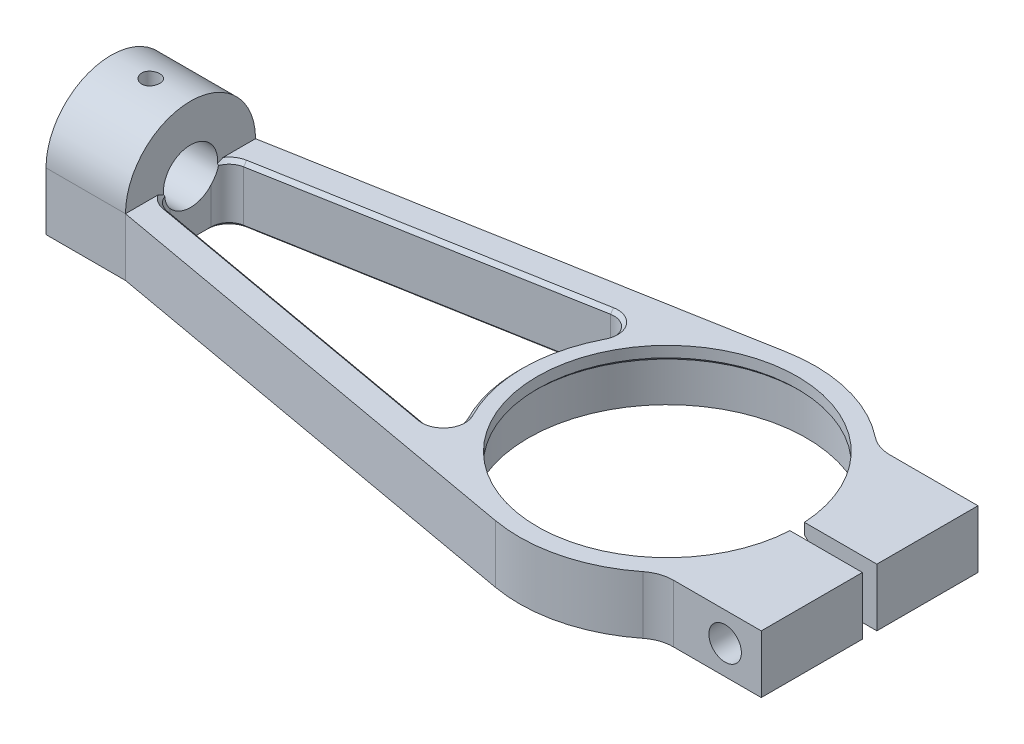
SolidWorks part; units mm, degrees
ref_plane "前视基准面" through (0, 0, 0) normal (0, 0, 1) x (1, 0, 0)
ref_plane "上视基准面" through (0, 0, 0) normal (0, 1, 0) x (1, 0, 0)
ref_plane "右视基准面" through (0, 0, 0) normal (1, 0, 0) x (0, 0, -1)
sketch "草图1" plane through (0, 0, 0) normal (0, 1, 0) x (1, 0, 0)
  line L0 (-55, 0) -> (55, 0) construction
  line L1 (56, -30) -> (27.9464, -30)
  line L2 (56, -30) -> (56, 30)
  line L3 (56, 30) -> (27.9464, 30)
  line L4 (27.9464, -30) -> (27.9464, 30) construction
  line L5 (56, -30) -> (40.9405, 2.2088) construction
  line L6 (56, 30) -> (40.9405, -2.2088) construction
  line L7 (-7.2316, 40.3572) -> (-132, 18)
  line L8 (-132, 18) -> (-132, -18)
  line L9 (-132, 0) -> (0, 0) construction
  line L10 (-7.2316, -40.3572) -> (-132, -18)
  line L11 (40.9405, 2.2088) -> (27.9464, 30) construction
  line L12 (40.9405, -2.2088) -> (27.9464, -30) construction
  line L13 (0, -55) -> (0, 55) construction
  line L14 (-132, -18) -> (-154, -18) construction
  line L15 (-132, -18) -> (-132, 18)
  line L16 (-132, 18) -> (-154, 18) construction
  line L17 (-154, -18) -> (-154, 18) construction
  arc A0 (-7.2316, -40.3572) -> (27.9464, -30) centre (0, 0) ccw
  arc A1 (-7.2316, 40.3572) -> (-41, 0) centre (0, 0) ccw construction
  arc A2 (-41, 0) -> (-7.2316, -40.3572) centre (0, 0) ccw construction
  arc A3 (40.9405, -2.2088) -> (40.9405, 2.2088) centre (0, 0) ccw construction
  arc A4 (27.9464, 30) -> (-7.2316, 40.3572) centre (0, 0) ccw
  arc A5 (40.9405, 2.2088) -> (27.9464, 30) centre (0, 0) ccw construction
  arc A6 (27.9464, -30) -> (40.9405, -2.2088) centre (0, 0) ccw construction
  point P3 (41.9732, 0)
  point P20 (-138.0209, 17.4084)
  point P22 (0, 0)
  dimension "D1" = 82
  dimension "D2" = 60
  dimension "D3" = 22
  dimension "D4" = 154
  dimension "D5" = 210
  dimension "D6" = 36
extrude "凸台-拉伸1" add sketch "草图1" along normal blind 16 contours L3 A4 L7 L8 L10 A0 L1 L2
sketch "草图2" plane through (0, 16, 0) normal (0, 1, 0) x (1, 0, 0)
  circle A0 centre (0, 0) radius 36
  dimension "D1" = 72
extrude "切除-拉伸1" cut sketch "草图2" against normal through all both and the other way through all
sketch "草图3" plane through (0, 0, 0) normal (0, -1, 0) x (1, 0, 0)
  circle A0 centre (0, 0) radius 38.5
  dimension "D1" = 77
extrude "切除-拉伸2" cut sketch "草图3" against normal blind 12 and the other way through all
sketch "草图4" plane through (0, 16, 0) normal (0, 1, 0) x (1, 0, 0)
  line L0 (27.9464, 0) -> (74.1701, 0)
  line L1 (27.9464, -30) -> (27.9464, 30) construction
  line L2 (-8.8, 0) -> (8.8, 0) construction
extrude "切除-拉伸-薄壁1" cut sketch "草图4" against normal through all and the other way through all thin thin type mid plane wall 4
sketch "草图5" plane through (0, 0, 30) normal (0, 0, 1) x (1, 0, 0)
  line L0 (56, 0) -> (27.9464, 0) construction
  line L1 (56, 16) -> (56, 0) construction
  circle A0 centre (46, 8) radius 4.5
  dimension "D1" = 9
  dimension "D2" = 8
  dimension "D3" = 10
extrude "切除-拉伸3" cut sketch "草图5" against normal up to next
hole_wizard "M8 螺纹孔1" positions "草图6" profile "草图7" tap size "M8" standard "GB" end condition up to next
sketch "草图6" plane through (0, 0, -2) normal (0, 0, 1) x (1, 0, 0)
  circle A0 centre (46, 8) radius 4.5 construction
  point P0 (46, 8)
sketch "草图7" plane through (46, 8, -2) normal (1, 0, 0) x (0, -1, 0)
  line L0 (0, 0) -> (0, 28)
  line L1 (0, 28) -> (3.4, 28)
  line L2 (3.4, 28) -> (3.4, 0)
  line L5 (3.4, 0) -> (0, 0)
  line L11 (0, -6.35) -> (0, 107.95) construction
  dimension "通孔螺纹孔钻头直径" = 6.8
  dimension "通孔螺纹孔钻头深度" = 28
cosmetic thread "孔螺纹线1" parameters "D2"=8
fillet "圆角1" radius 10 2 edges at (27.9464, 8, -30) (27.9464, 8, 30)
sketch "草图11" plane through (-132, 0, 0) normal (-1, 0, 0) x (0, 0, 1)
  line L1 (-18, 0) -> (18, 0)
  line L2 (-18, 0) -> (-18, 16)
  line L3 (-18, 16) -> (18, 16) construction
  line L4 (18, 0) -> (18, 16)
  arc A0 (18, 16) -> (-18, 16) centre (0, 16) ccw
  arc A1 (-18, 16) -> (18, 16) centre (0, 16) ccw construction
  dimension "D1" = 16
extrude "凸台-拉伸2" add sketch "草图11" along normal up to vertex (22 mm away) up to point (-154, 0, 18)
sketch "草图13" plane through (0, 16, 0) normal (0, 1, 0) x (1, 0, 0)
  line L37 (0, 0) -> (-130.589, 0) construction
  line L38 (-5.8206, 32.4826) -> (-130.589, 10.1254)
  line L39 (-41.7449, 26.0454) -> (-127.8819, 10.6105)
  line L40 (-18.7, 0) -> (18.7, 0) construction
  line L41 (-132, -18) -> (-132, 18) construction
  line L42 (-132, 5.6889) -> (-132, -5.6889)
  line L43 (-132, 18) -> (-132, -18) construction
  line L44 (-5.8206, 32.4826) -> (-29.7701, 28.1911) construction
  line L45 (-5.8206, -32.4826) -> (-29.7701, -28.1911) construction
  line L46 (-41.7449, -26.0454) -> (-127.8819, -10.6105)
  arc A10 (-36.4214, 18.8277) -> (-36.4214, -18.8277) centre (0, 0) ccw
  arc A11 (25.4349, 32.1569) -> (-7.2316, 40.3572) centre (0, 0) ccw construction
  arc A12 (-41, 0) -> (-29.7701, 28.1911) centre (0, 0) ccw construction
  arc A13 (-127.8819, 10.6105) -> (-132, 5.6889) centre (-127, 5.6889) ccw
  arc A14 (-127.8819, -10.6105) -> (-132, -5.6889) centre (-127, -5.6889) cw
  arc A15 (-36.4214, -18.8277) -> (-41.7449, -26.0454) centre (-40.863, -21.1237) cw
  arc A16 (-41.7449, 26.0454) -> (-36.4214, 18.8277) centre (-40.863, 21.1237) cw
  point P18 (-132, 0)
  point P20 (-132, 9.8726)
  point P24 (-132, -9.8726)
  dimension "D2" = 5
  dimension "D1" = 8
extrude "切除-拉伸4" cut sketch "草图13" against normal up to next
chamfer "倒角1" distance 1 angle 45 15 edges at (-130.8347, 16, 8.8975) (-84.8134, 16, 18.3279) (-36.8392, 16, 24.0916) (-41, 16, 0) (-36.8392, 16, -24.0916) (-130.8347, 16, -8.8975) (-84.8134, 16, -18.3279) (-84.8134, 0, 18.3279) (-130.8347, 0, 8.8975) (-36.8392, 0, 24.0916) (-132, 0, 0) (-41, 0, 0) (-130.8347, 0, -8.8975) (-36.8392, 0, -24.0916) (-84.8134, 0, -18.3279)
chamfer "倒角2" distance 1 angle 45 1 edges at (-36, 12, 0)
sketch "草图12" plane through (-154, 0, 0) normal (-1, 0, 0) x (0, 0, 1)
  circle A0 centre (0, 16) radius 7.5
  dimension "D1" = 15
extrude "切除-拉伸5" cut sketch "草图12" against normal up to next
hole_wizard "Ø5.0mm 暗销孔1" positions "3D草图1" profile "草图14" hole size "Ø5.0" standard "GB" end condition through all
sketch3d "3D草图1"
  point P0 (-143, 34, 0)
  dimension "D1" = 11
sketch "草图14" plane through (-143, 34, 0) normal (1, 0, 0) x (0, 0, 1)
  line L0 (0, 0) -> (0, 34)
  line L1 (0, 34) -> (2.5, 34)
  line L2 (2.5, 34) -> (2.5, 0)
  line L5 (2.5, 0) -> (0, 0)
  line L11 (0, -6.35) -> (0, 107.95) construction
  dimension "通孔孔直径" = 5
  dimension "通孔孔深度" = 34
chamfer "倒角3" distance 1 angle 45 1 edges at (-154, 16, 7.5)
